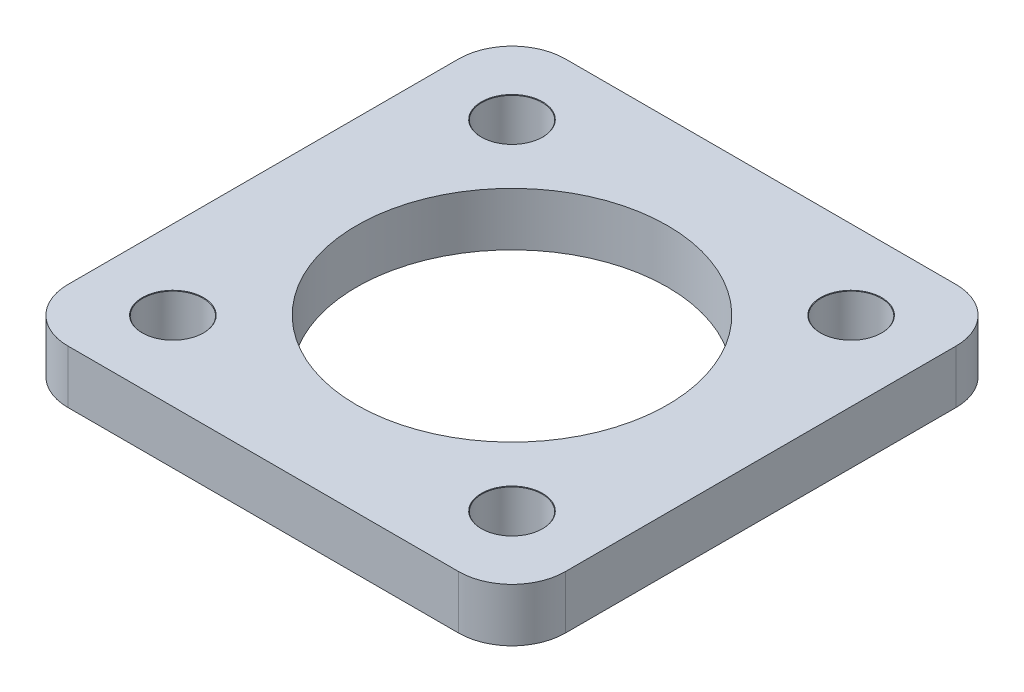
SolidWorks part; units mm, degrees
ref_plane "Front Plane" through (0, 0, 0) normal (0, 0, 1) x (1, 0, 0)
ref_plane "Top Plane" through (0, 0, 0) normal (0, 1, 0) x (1, 0, 0)
ref_plane "Right Plane" through (0, 0, 0) normal (1, 0, 0) x (0, 0, -1)
sketch "Sketch1" plane through (0, 0, 0) normal (0, 1, 0) x (1, 0, 0)
  line L1 (14, 14) -> (-14, 14)
  line L2 (14, 14) -> (14, -14)
  line L3 (14, -14) -> (-14, -14)
  line L4 (-14, 14) -> (-14, -14)
  line L5 (14, 14) -> (-14, -14) construction
  line L6 (14, -14) -> (-14, 14) construction
  point P0 (0, 0)
  dimension "D1" = 28
extrude "Boss-Extrude1" add sketch "Sketch1" along normal blind 3
sketch "Sketch2" plane through (0, 3, 0) normal (0, 1, 0) x (1, 0, 0)
  circle A0 centre (0, 0) radius 8.75
  dimension "D1" = 17.5
extrude "Cut-Extrude1" cut sketch "Sketch2" against normal through all
sketch "Sketch7" plane through (0, 3, 0) normal (0, 1, 0) x (1, 0, 0)
  line L0 (9.5459, 9.5459) -> (0, 0)
  circle A0 centre (0, 0) radius 13.5
  point P5 (9.5459, 9.5459)
  point P16 (9.5459, -9.5459)
  point P17 (-9.5459, -9.5459)
  point P18 (-9.5459, 9.5459)
  dimension "D1" = 27
  dimension "D2" = 45
  dimension "D3" = 4
hole_wizard "M3 Clearance Hole1" positions "Sketch7" profile "Sketch6" hole size "M3" standard "DIN" end condition up to next
sketch "Sketch6" plane through (-9.5459, 3, -9.5459) normal (1, 0, 0) x (0, 0, 1)
  line L0 (0, 0) -> (0, 3)
  line L1 (0, 3) -> (1.7, 3)
  line L2 (1.7, 3) -> (1.7, 0.025)
  line L3 (1.7, 0.025) -> (1.725, 0)
  line L5 (1.725, 0) -> (0, 0)
  line L6 (-1.7, 0.025) -> (-1.725, 0) construction
  line L11 (0, -6.35) -> (0, 107.95) construction
  dimension "Thru Hole Dia." = 3.4
  dimension "Thru Hole Depth" = 3
  dimension "Near C'Sink Dia." = 3.45
  dimension "Near C'Sink Angle" = 90
fillet "Fillet1" radius 3 4 edges at (14, 1.5, -14) (14, 1.5, 14) (-14, 1.5, 14) (-14, 1.5, -14)
